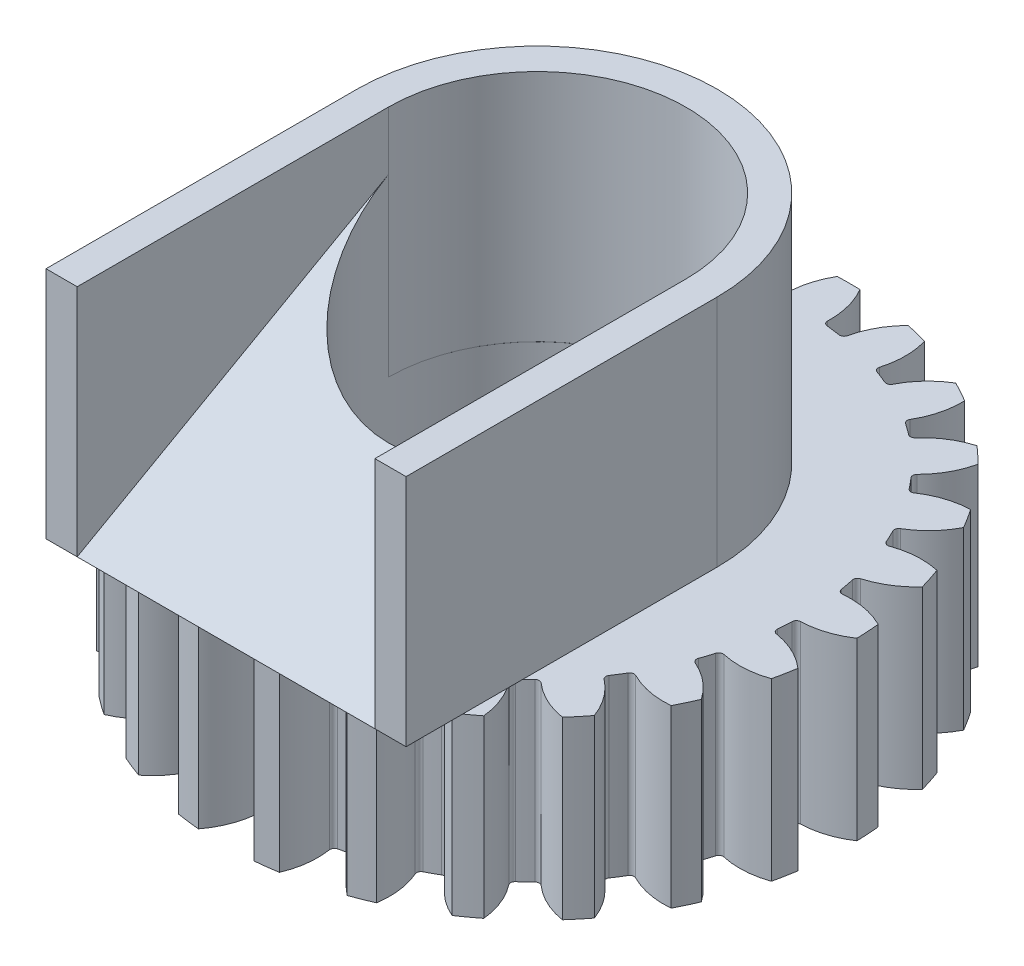
SolidWorks part; units mm, degrees
ref_plane "Front Plane" through (0, 0, 0) normal (0, 0, 1) x (1, 0, 0)
ref_plane "Top Plane" through (0, 0, 0) normal (0, 1, 0) x (1, 0, 0)
ref_plane "Right Plane" through (0, 0, 0) normal (1, 0, 0) x (0, 0, -1)
sketch "Sketch3" plane through (0, 0, 0) normal (0, 0, 1) x (1, 0, 0)
  line L0 (-0.0769, 25.8145) -> (20.8731, 25.8145)
  line L1 (20.8731, 25.8145) -> (20.8731, 3.3145)
  line L2 (20.8731, 3.3145) -> (-0.0769, 3.3145)
  line L5 (-0.0769, 3.3145) -> (-0.0769, 25.8145)
  line L6 (-19.1269, 24.9434) -> (-19.1269, -20.3377) construction
  dimension "D1" = 19.05
  dimension "D2" = 40
  dimension "D4" = 22.5
revolve "Revolve1" add sketch "Sketch3" angle 360 about L6
sketch "Sketch5" plane through (0, 3.3145, 0) normal (0, -1, 0) x (1, 0, 0)
  line L0 (-19.1269, 0) -> (-19.1269, 40) construction
  line L1 (-20.5562, 33.9699) -> (-19.1269, 0) construction
  line L2 (-19.1269, 31.4562) -> (-23.8282, 44.3728) construction
  arc A0 (-15.5608, 39.8407) -> (-22.693, 39.8407) centre (-19.1269, 0) ccw
  arc A1 (-17.1279, 36.946) -> (-21.1259, 36.946) centre (-19.1269, 0) ccw construction
  arc A2 (-17.6976, 33.9699) -> (-20.5562, 33.9699) centre (-19.1269, 0) ccw
  arc A3 (-22.693, 39.8407) -> (-20.5562, 33.9699) centre (-30.8833, 33.5354) cw
  arc A4 (-15.5608, 39.8407) -> (-17.6976, 33.9699) centre (-7.3705, 33.5354) ccw
  point P14 (-21.1704, 37.0706)
  dimension "D1" = 74
  dimension "D2" = 80
  dimension "D3" = 68
  dimension "D4" = 20
  dimension "D5" = 4
extrude "Cut-Extrude1" cut sketch "Sketch5" against normal through all
fillet "Fillet1" radius 0.57 2 edges at (-20.5562, 14.5645, 33.9699) (-17.6976, 14.5645, 33.9699)
pattern_circular "CirPattern1" count 25 over 360 about axis through (-19.1269, 0, 0) along (0, 1, 0) of "Fillet1", "Cut-Extrude1"
sketch "Sketch6" plane through (0, 25.8145, 0) normal (0, 1, 0) x (1, 0, 0)
  line L0 (-42.1769, 0) -> (-42.1769, -39.9017)
  line L1 (-42.1769, -39.9017) -> (-38.1769, -39.9017)
  line L2 (-38.1769, -39.9017) -> (-38.1769, 0)
  line L3 (0, 0) -> (0, -39.9017)
  line L4 (0, -39.9017) -> (4, -39.9017)
  line L5 (4, -39.9017) -> (4, 0)
  arc A0 (-38.1769, 0) -> (0, 0) centre (-19.0885, 0) cw
  circle A1 centre (-19.1269, 0) radius 19.05 construction
  arc A2 (-42.1769, 0) -> (4, 0) centre (-19.0885, 0) cw
  dimension "D1" = 19.0885
  dimension "D2" = 4
  dimension "D3" = 4
extrude "Boss-Extrude1" add sketch "Sketch6" along normal blind 30
sketch "Sketch8" plane through (-38.1769, 0, 0) normal (1, 0, 0) x (0, 0, -1)
  line L2 (0, 25.8145) -> (-39.9017, 25.8145)
  line L3 (-39.9017, 25.8145) -> (0, 48.3145)
  line L4 (0, 48.3145) -> (0, 25.8145)
  line L5 (0, 55.8145) -> (0, 25.8145) construction
  dimension "D1" = 22.5
extrude "Boss-Extrude2" add sketch "Sketch8" along normal blind 39
sketch "Sketch9" plane through (0, 25.8145, 0) normal (0, -1, 0) x (-1, 0, 0)
  line L0 (0.0769, 0) -> (38.1769, 0) construction
  circle A0 centre (19.1269, 0) radius 19.05
extrude "Cut-Extrude2" cut sketch "Sketch9" against normal through all
